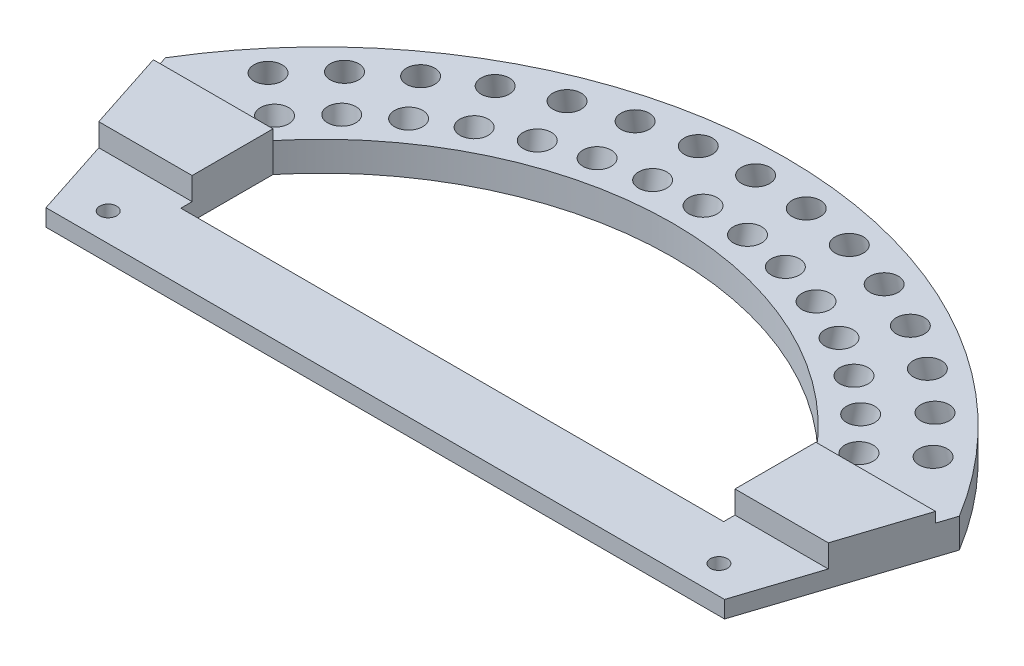
SolidWorks part; units mm, degrees
ref_plane "Front Plane" through (0, 0, 0) normal (0, 0, 1) x (1, 0, 0)
ref_plane "Top Plane" through (0, 0, 0) normal (0, 1, 0) x (1, 0, 0)
ref_plane "Right Plane" through (0, 0, 0) normal (1, 0, 0) x (0, 0, -1)
sketch "Sketch1" plane through (0, 0, 0) normal (0, 1, 0) x (1, 0, 0)
  line L0 (0, 0) -> (0, 31.147) construction
  line L1 (-60, -40) -> (60, -40) construction
  line L2 (-60, -40) -> (-60, 40) construction
  line L3 (-60, 40) -> (60, 40) construction
  line L4 (60, -40) -> (60, 40) construction
  line L5 (-60, -40) -> (60, 40) construction
  line L6 (-60, 40) -> (60, -40) construction
  line L7 (48, 23.11) -> (48, 9.16)
  line L8 (-60, 23.11) -> (-48, 23.11)
  line L9 (-60, 23.11) -> (-60, 9.16)
  line L10 (-60, 9.16) -> (-48, 9.16)
  line L11 (-48, 23.11) -> (-48, 9.16)
  line L12 (60, 9.16) -> (48, 9.16)
  line L13 (60, 23.11) -> (60, 9.16)
  line L14 (60, 23.11) -> (48, 23.11)
  line L15 (-47.5161, 40) -> (47.5161, 40)
  line L16 (60, 11.27) -> (-60, 11.27)
  line L17 (-60, 11.27) -> (-70.1997, 42.5937)
  line L18 (60, 11.27) -> (70.1997, 42.5937)
  line L19 (48, 23.11) -> (48, 39.418)
  line L20 (-48, 23.11) -> (-48, 39.418)
  line L21 (48, 23.11) -> (-48, 23.11)
  circle A0 centre (-54, 16.27) radius 1.5
  circle A1 centre (-54, -16.28) radius 1.5 construction
  circle A2 centre (54, -16.28) radius 1.5 construction
  circle A3 centre (54, 16.27) radius 1.5
  circle A4 centre (0, 0) radius 72.111 construction
  circle A5 centre (0, 0) radius 62.111
  circle A6 centre (0, 0) radius 82.111
  point P0 (0, 0)
  dimension "D5" = 3
  dimension "D6" = 3
  dimension "D7" = 10
  dimension "D8" = 10
  dimension "D1" = 80
  dimension "D2" = 120
  dimension "D3" = 23.73
  dimension "D4" = 32.55
  dimension "D9" = 12
  dimension "D10" = 6
  dimension "D11" = 7.11
  dimension "D12" = 6.84
  dimension "D13" = 5
extrude "Boss-Extrude1" add sketch "Sketch1" along normal blind 3
sketch "Sketch2" plane through (0, 3, 0) normal (0, 1, 0) x (1, 0, 0)
  line L2 (-48, 39.418) -> (48, 39.418) construction
  line L4 (48, 23.11) -> (48, 39.418) construction
  line L5 (-88.4384, 39.418) -> (88.4384, 39.418)
  circle A0 centre (0, 0) radius 62.111
  circle A1 centre (0, 0) radius 82.3372
  point P15 (0, 39.418)
extrude "Boss-Extrude2" add sketch "Sketch2" along normal blind 2.2
sketch "Sketch3" plane through (0, 3, 0) normal (0, 1, 0) x (1, 0, 0)
  line L0 (-64.5066, 25.11) -> (64.5066, 25.11)
  line L1 (-60, 11.27) -> (-69.1657, 39.418) construction
  line L2 (60, 11.27) -> (69.1657, 39.418) construction
  line L3 (64.5066, 25.11) -> (69.1657, 39.418)
  line L6 (-48, 39.418) -> (-48, 25.11)
  line L8 (48, 25.11) -> (48, 39.418)
  line L9 (48, 23.11) -> (-48, 23.11) construction
  line L10 (48, 23.11) -> (48, 39.418) construction
  line L11 (-48, 23.11) -> (-48, 39.418) construction
  line L12 (-69.1657, 39.418) -> (-64.5066, 25.11)
  line L13 (48, 39.418) -> (-48, 39.418) construction
  line L14 (-69.1657, 39.418) -> (69.1657, 39.418)
  circle A0 centre (0, 0) radius 62.111
  point P36 (0, 39.418)
  dimension "D1" = 2
extrude "Boss-Extrude3" add sketch "Sketch3" along normal blind 4
sketch "Sketch4" plane through (0, 5.2, 0) normal (0, -1, 0) x (1, 0, 0)
  line L0 (0, -62.111) -> (0, -82.111) construction
  line L1 (-4.3078, -72.111) -> (4.3078, -72.111) construction
  line L2 (0, -74.261) -> (0, -69.961) construction
  line L3 (0, 0) -> (-55.7281, -45.7644) construction
  line L4 (0, 0) -> (0, -48.9342) construction
  circle A1 centre (0, 0) radius 62.111
  circle A2 centre (0, 0) radius 82.111
  circle A3 centre (0, -67.461) radius 2.5
  circle A4 centre (0, -76.761) radius 2.5
  circle A5 centre (0, 0) radius 72.111 construction
  point P18 (0, -72.111)
  point P42 (0, 0)
  point P52 (0, 0)
  point P81 (0, 0)
  dimension "D1" = 5
  dimension "D2" = 9.3
  dimension "D3" = 50.607
  dimension "D5" = 10
  dimension "D4" = 20
ref_plane "Plane1" through (0, 0, 0) normal (-1, 0, 0) x (0, 0, 1)
sketch3d "3DSketch1" [suppressed]
  line L0 (0, 5.2, -72.111) -> (0, 20.2, -72.111) construction
  line L1 (0, 20.2, -72.111) -> (0, -33.0638, -81.5029) construction
  line L2 (0, 20.2, -72.111) -> (0, -36.8854, -62.0453) construction
  line L3 (0, 0, 0) -> (0, 5.2, -72.111) construction
  line L32 (0, 0, 0) -> (0, 15, 0)
  circle A0 centre (0, 0, 0) radius 72.2983 construction
  circle A1 centre (0, 5.2, -72.111) radius 4.11
  point P7 (0, 72.111, 5.2)
  point P20 (0, 9.2992, -71.8127)
  dimension "D1" = 15
  dimension "D2" = 10
  dimension "D3" = 10
sketch3d "3DSketch2"
  line L0 (0, 0, 0) -> (0, 20.5578, 0) construction
  line L1 (0, 5.2, -100.5185) -> (0, 5.2, 0) construction
  line L2 (0, 5.2, 0) -> (0, 0, 0) construction
  line L3 (0, 7, -72.111) -> (0, 22, -72.111) construction
  line L4 (0, 5.2, -72.111) -> (0, 7, -72.111) construction
  line L5 (0, 22, -72.111) -> (0, 5.2, -69.1487) construction
  line L6 (0, 7, 0) -> (0, 7, -100) construction
  line L7 (0, 22, -72.111) -> (0, 5.2, -75.0733) construction
  line L8 (0, -29.2683, -61.3833) -> (0, 39.6683, -73.5387) construction
  line L9 (0, -29.2683, -82.8387) -> (0, 39.6683, -70.6833) construction
  line L10 (-0.0436, -39.1163, -57.1472) -> (-0.0436, 49.5163, -72.7756)
  line L11 (0, -29.2683, -63.8833) -> (0, 39.6683, -76.0387)
  line L12 (0, -39.1163, -87.0421) -> (0, 49.5163, -71.4138)
  line L13 (0, -29.2683, -80.3387) -> (0, 39.6683, -68.1833)
  circle A0 centre (0, 5.2, -67.461) radius 2.5
  circle A1 centre (0, 5.2, -76.761) radius 2.5
  circle A2 centre (0, 5.2, 0) radius 62.111 construction
  circle A3 centre (0, 5.2, 0) radius 82.111 construction
  circle A4 centre (0, 5.2, 0) radius 72.111 construction
  point P9 (0, 7.7, -67.461)
  point P12 (0, 7.7, -76.761)
  point P14 (0, 67.311, 0)
  point P17 (0, 87.311, 0)
  point P20 (0, 77.311, 0)
  point P21 (0, 5.2, -72.111)
  point P34 (0, 5.2, -67.461)
  point P37 (0, 5.2, -76.761)
  point P38 (-0.0436, 5.2, -64.9614)
  point P41 (0, 5.2, -69.961)
  point P44 (0, 5.2, -79.228)
  point P47 (0, 5.2, -74.261)
  dimension "D1" = 5
  dimension "D2" = 5
  dimension "D3" = 9.3
  dimension "D4" = 20
  dimension "D5" = 10
  dimension "D6" = 4.65
  dimension "D7" = 1.8
  dimension "D8" = 15
  dimension "D9" = 10
  dimension "D10" = 10
extrude "Cut-Extrude2" cut sketch "Sketch4" along direction (0, 0.9848, -0.1736) on the side of the normal blind 15.2 contours A3
sketch "Sketch6" plane through (0, 5.2, 0) normal (0, 1, 0) x (1, 0, 0)
  line L0 (0, 13.0181) -> (0, -13.0181)
  line L1 (16.8951, 0) -> (-16.8951, 0)
  point P4 (0, 0)
  point P7 (0, 0)
sketch "Sketch7" plane through (0, 5.2, 0) normal (0, 1, 0) x (1, 0, 0)
  line L0 (0, 0) -> (0, 100) construction
  circle A0 centre (0, 67.461) radius 2.5
  circle A1 centre (0, 76.761) radius 2.5
  circle A2 centre (0, 0) radius 82.111 construction
  circle A3 centre (0, 0) radius 62.111 construction
  circle A4 centre (0, 0) radius 72.111 construction
  dimension "D1" = 5
  dimension "D3" = 4.65
  dimension "D2" = 9.3
extrude "Cut-Extrude3" cut sketch "Sketch7" along direction (0, 0.9848, 0.1736) on the side against the normal blind 13.5 contours L0 A1 | A1 L0
pattern_circular "CirPattern1" count 8 every 7.143 of "Cut-Extrude2"
pattern_circular "CirPattern2" count 8 every 7.143 of "Cut-Extrude2"
pattern_circular "CirPattern3" count 8 every 7.143 of "Cut-Extrude3"
pattern_circular "CirPattern4" count 8 every 7.143 of "Cut-Extrude3"
